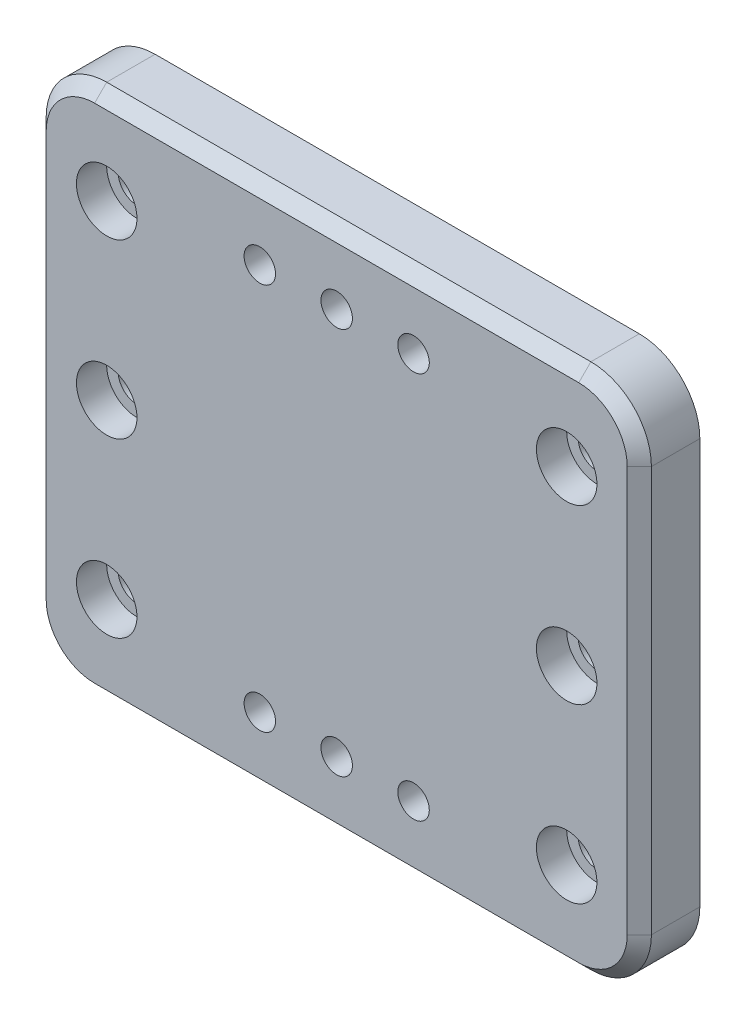
SolidWorks part; units mm, degrees
ref_plane "前视基准面" through (0, 0, 0) normal (0, 0, 1) x (1, 0, 0)
ref_plane "上视基准面" through (0, 0, 0) normal (0, 1, 0) x (1, 0, 0)
ref_plane "右视基准面" through (0, 0, 0) normal (1, 0, 0) x (0, 0, -1)
sketch "草图1" plane through (0, 0, 0) normal (0, 0, 1) x (1, 0, 0)
  line L1 (-50, 43.5) -> (50, 43.5)
  line L2 (-50, 43.5) -> (-50, -43.5)
  line L3 (-50, -43.5) -> (50, -43.5)
  line L4 (50, 43.5) -> (50, -43.5)
  line L5 (-50, 43.5) -> (50, -43.5) construction
  line L6 (-50, -43.5) -> (50, 43.5) construction
  point P0 (0, 0)
  dimension "D1" = 100
  dimension "D2" = 87
extrude "凸台-拉伸1" add sketch "草图1" along normal blind 10
fillet "圆角1" radius 10 4 edges at (50, -43.5, 5) (-50, -43.5, 5) (50, 43.5, 5) (-50, 43.5, 5)
sketch "草图2" plane through (0, 0, 10) normal (0, 0, 1) x (1, 0, 0)
  line L0 (0, 43.5) -> (0, 32) construction
  line L1 (40, 43.5) -> (-40, 43.5) construction
  line L2 (0, 32) -> (-12.7, 32) construction
  line L3 (0, 32) -> (0, -32) construction
  line L4 (0, -32) -> (-12.7, -32) construction
  line L5 (0, -32) -> (12.7, -32) construction
  circle A0 centre (0, 32) radius 2.6
  circle A1 centre (-12.7, 32) radius 2.6
  circle A2 centre (12.7, 32) radius 2.6
  circle A3 centre (-12.7, -32) radius 2.6
  circle A4 centre (0, -32) radius 2.6
  circle A5 centre (12.7, -32) radius 2.6
  point P16 (0, 0)
  dimension "D1" = 12.7
  dimension "D2" = 0
  dimension "D3" = 64
extrude "切除-拉伸1" cut sketch "草图2" against normal blind 10
sketch "草图3" plane through (0, 0, 10) normal (0, 0, 1) x (1, 0, 0)
  line L0 (-50, 0) -> (-38, 0) construction
  line L1 (-50, 33.5) -> (-50, -33.5) construction
  line L2 (-38, 0) -> (-38, 28.5) construction
  line L3 (-38, 0) -> (-38, -28.5) construction
  line L4 (0, 0) -> (0, 10) construction
  line L6 (-40, -43.5) -> (40, -43.5) construction
  line L7 (40, 43.5) -> (-40, 43.5) construction
  circle A0 centre (-38, 28.5) radius 5
  circle A1 centre (-38, 0) radius 5
  circle A2 centre (-38, -28.5) radius 5
  circle A3 centre (38, -28.5) radius 5
  circle A4 centre (38, 0) radius 5
  circle A5 centre (38, 28.5) radius 5
  dimension "D1" = 76
  dimension "D2" = 15
  dimension "D3" = 15
extrude "切除-拉伸2" cut sketch "草图3" against normal blind 5
sketch "草图4" plane through (0, 0, 5) normal (0, 0, 1) x (1, 0, 0)
  circle A0 centre (-38, 28.5) radius 3.1
  circle A1 centre (-38, 0) radius 3.1
  circle A2 centre (-38, -28.5) radius 3.1
  circle A3 centre (38, 28.5) radius 3.1
  circle A4 centre (38, 0) radius 3.1
  circle A5 centre (38, -28.5) radius 3.1
extrude "切除-拉伸3" cut sketch "草图4" against normal blind 5
chamfer "倒角1" distance 1 angle 45 6 edges at (41.1, 28.5, 0) (41.1, 0, 0) (41.1, -28.5, 0) (-34.9, -28.5, 0) (-34.9, 0, 0) (-34.9, 28.5, 0)
chamfer "倒角2" distance 2 angle 45 8 edges at (50, 0, 10) (47.0711, 40.5711, 10) (47.0711, -40.5711, 10) (0, 43.5, 10) (0, -43.5, 10) (-47.0711, 40.5711, 10) (-47.0711, -40.5711, 10) (-50, 0, 10)
